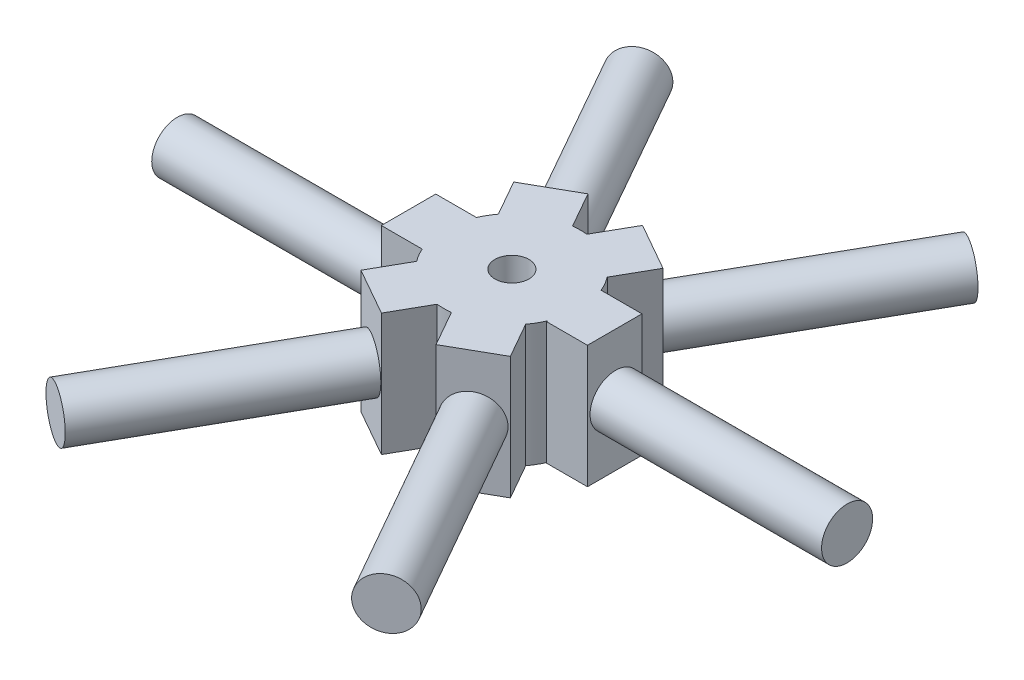
SolidWorks part; units mm, degrees
ref_plane "Front Plane" through (0, 0, 0) normal (0, 0, 1) x (1, 0, 0)
ref_plane "Top Plane" through (0, 0, 0) normal (0, 1, 0) x (1, 0, 0)
ref_plane "Right Plane" through (0, 0, 0) normal (1, 0, 0) x (0, 0, -1)
sketch "Sketch1" plane through (0, 0, 0) normal (0, 1, 0) x (1, 0, 0)
  circle A0 centre (0, 0) radius 3.175
  circle A1 centre (0, 0) radius 12.7
  dimension "D1" = 6.35
  dimension "D2" = 25.4
extrude "Boss-Extrude1" add sketch "Sketch1" along normal blind 22.86
ref_plane "Plane1" through (0, 11.43, 0) normal (0, -1, 0) x (-1, 0, 0)
sketch3d "3DSketch2"
  circle A0 centre (0, 0, 0) radius 12.7 construction
  circle A1 centre (0, 0, 0) radius 12.7
  point P2 (0, 12.7, 0)
  point P4 (0, 12.7, 0)
sketch "Sketch2" plane through (0, 11.43, 0) normal (0, -1, 0) x (-1, 0, 0)
  circle A0 centre (0, 0) radius 12.7 construction
  circle A1 centre (0, 0) radius 12.7
  circle A2 centre (0, 0) radius 12.7 construction
  circle A3 centre (0, 0) radius 12.7
  circle A4 centre (0, 0) radius 12.7
  point P7 (-12.7, 0)
sketch "Sketch3" plane through (0, 0, 0) normal (0, 0, 1) x (1, 0, 0)
  line L0 (12.7, 22.86) -> (-12.7, 22.86) construction
  point P0 (0, 22.86)
  point P1 (0, 0)
ref_plane "Plane2" through (0, 0, 0) normal (0, 1, 0) x (1, 0, 0)
sketch "Sketch4" plane through (0, 0, 0) normal (0, 1, 0) x (1, 0, 0)
  line L0 (-11.6219, 5.0393) -> (11.7103, 4.9153) construction
  line L2 (-11.6219, -5.1207) -> (11.7103, -5.2447) construction
  line L3 (-10.16, 7.62) -> (1.3382, -12.6293) construction
  line L6 (1.3382, -12.6293) -> (-1.3217, 12.631) construction
  line L15 (11.7103, -5.2447) -> (11.7103, 4.9153)
  line L16 (11.7103, 4.9153) -> (19.3303, 4.9153)
  line L17 (19.3303, 4.9153) -> (19.3303, -5.2447)
  line L18 (19.3303, -5.2447) -> (11.7103, -5.2447)
  line L24 (-11.6219, 5.0393) -> (-11.6219, -5.1207)
  line L28 (-11.6219, -5.1207) -> (-19.2419, -5.1207)
  line L29 (-19.2419, -5.1207) -> (-19.2419, 5.0393)
  line L30 (-19.2419, 5.0393) -> (-11.6219, 5.0393)
  line L36 (-10.16, 7.62) -> (-1.3217, 12.631)
  line L37 (-10.16, 7.62) -> (-13.9183, 14.2487)
  line L38 (-13.9183, 14.2487) -> (-5.08, 19.2597)
  line L39 (-5.08, 19.2597) -> (-1.3217, 12.631)
  line L40 (-1.3217, 12.631) -> (10.1699, -7.6068) construction
  line L41 (1.3382, 12.6293) -> (10.1699, 7.6068)
  line L42 (10.1699, 7.6068) -> (13.9368, 14.2306)
  line L43 (13.9368, 14.2306) -> (5.1051, 19.2531)
  line L44 (5.1051, 19.2531) -> (1.3382, 12.6293)
  line L45 (10.1699, -7.6068) -> (10.1699, 7.6068) construction
  line L46 (-10.16, -7.62) -> (-1.3217, -12.631)
  line L47 (-1.3217, -12.631) -> (-5.08, -19.2597)
  line L48 (-5.08, -19.2597) -> (-13.9183, -14.2487)
  line L49 (-13.9183, -14.2487) -> (-10.16, -7.62)
  line L50 (-10.16, -7.62) -> (-13.9183, -14.2487)
  line L51 (10.1699, 7.6068) -> (-1.3382, -12.6293) construction
  line L52 (1.3382, -12.6293) -> (10.1699, -7.6068)
  line L53 (10.1699, -7.6068) -> (13.9368, -14.2306)
  line L54 (13.9368, -14.2306) -> (5.1051, -19.2531)
  line L55 (5.1051, -19.2531) -> (1.3382, -12.6293)
  line L56 (10.1699, 7.6068) -> (10.123, 7.6691)
  line L57 (1.3382, 12.6293) -> (-10.16, -7.62) construction
  circle A0 centre (0, 0) radius 12.7 construction
  circle A1 centre (0, 0) radius 12.7 construction
  dimension "D2" = 7.62
  dimension "D3" = 10.16
  dimension "D4" = 7.62
  dimension "D5" = 10.16
  dimension "D6" = 7.62
  dimension "D7" = 7.62
  dimension "D8" = 10.16
  dimension "D9" = 7.62
  dimension "D10" = 7.62
  dimension "D11" = 10.16
  dimension "D12" = 10.16
  dimension "D13" = 10.16
extrude "Boss-Extrude2" add sketch "Sketch4" along normal blind 22.86
ref_plane "Plane3" through (21.8703, 0, 0) normal (1, 0, 0) x (0, 0, -1)
sketch "Sketch5" plane through (21.8703, 0, 0) normal (1, 0, 0) x (0, 0, -1)
  line L0 (0, 26.8622) -> (0, -1.3028) construction
  line L1 (-8.4495, 11.43) -> (4.9153, 11.43) construction
  line L2 (-12.7, 11.43) -> (12.7, 11.43) construction
  line L3 (4.9153, 22.86) -> (4.9153, 0) construction
  point P9 (0, 11.43)
ref_plane "Plane4" through (-21.7819, 0, 0) normal (-1, 0, 0) x (0, 0, 1)
sketch "Sketch8" plane through (-21.7819, 0, 0) normal (-1, 0, 0) x (0, 0, 1)
  circle A0 centre (0, 11.43) radius 3
extrude "Cut-Extrude1" cut sketch "Sketch8" against normal through all both and the other way through all
ref_plane "Plane5" through (10.7766, 0, -18.9498) normal (0.4943, 0, -0.8693) x (-0.8693, 0, -0.4943)
sketch "Sketch9" plane through (10.7766, 0, -18.9498) normal (0.4943, 0, -0.8693) x (-0.8693, 0, -0.4943)
  line L0 (-12.7, 11.43) -> (12.7, 11.43) construction
  circle A0 centre (0, 11.43) radius 3
extrude "Cut-Extrude2" cut sketch "Sketch9" against normal through all both
ref_plane "Plane6" through (10.7766, 0, 18.9498) normal (0.4943, 0, 0.8693) x (0.8693, 0, -0.4943)
sketch "Sketch10" plane through (10.7766, 0, 18.9498) normal (0.4943, 0, 0.8693) x (0.8693, 0, -0.4943)
  line L0 (-12.7, 11.43) -> (12.7, 11.43) construction
  circle A0 centre (0, 11.43) radius 3
extrude "Cut-Extrude3" cut sketch "Sketch10" against normal through all both
sketch "Sketch14" plane through (21.8703, 0, 0) normal (1, 0, 0) x (0, 0, -1)
  circle A0 centre (0, 11.43) radius 4.7625
extrude "Boss-Extrude3" add sketch "Sketch14" along normal blind 40.64 and the other way blind 2.54
sketch "Sketch15" plane through (10.7766, 0, 18.9498) normal (0.4943, 0, 0.8693) x (0.8693, 0, -0.4943)
  line L0 (-12.7, 11.43) -> (12.7, 11.43) construction
  circle A0 centre (0, 11.43) radius 4.7625
extrude "Boss-Extrude4" add sketch "Sketch15" along normal blind 40.64 and the other way blind 2.54
sketch "Sketch16" plane through (-21.7819, 0, 0) normal (-1, 0, 0) x (0, 0, 1)
  circle A0 centre (0, 11.43) radius 4.7625
extrude "Boss-Extrude5" add sketch "Sketch16" along normal blind 40.64 and the other way blind 2.54
sketch "Sketch17" plane through (10.7766, 0, -18.9498) normal (0.4943, 0, -0.8693) x (-0.8693, 0, -0.4943)
  line L0 (-12.7, 11.43) -> (12.7, 11.43) construction
  circle A0 centre (0, 11.43) radius 4.7625
extrude "Boss-Extrude6" add sketch "Sketch17" along normal blind 40.64 and the other way blind 2.54
ref_plane "Plane7" through (-9.4991, 0, -16.7542) normal (-0.4932, 0, -0.8699) x (-0.8699, 0, 0.4932)
sketch "Sketch18" plane through (-9.4991, 0, -16.7542) normal (-0.4932, 0, -0.8699) x (-0.8699, 0, 0.4932)
  line L0 (-12.7, 11.43) -> (12.7, 11.43) construction
  circle A0 centre (0, 11.43) radius 4.7625
extrude "Boss-Extrude7" add sketch "Sketch18" along normal blind 43.18
ref_plane "Plane8" through (-9.4991, 0, 16.7542) normal (-0.4932, 0, 0.8699) x (0.8699, 0, 0.4932)
sketch "Sketch19" plane through (-9.4991, 0, 16.7542) normal (-0.4932, 0, 0.8699) x (0.8699, 0, 0.4932)
  line L0 (-12.7, 11.43) -> (12.7, 11.43) construction
  circle A0 centre (0, 11.43) radius 4.7625
extrude "Boss-Extrude8" add sketch "Sketch19" along normal blind 43.18
